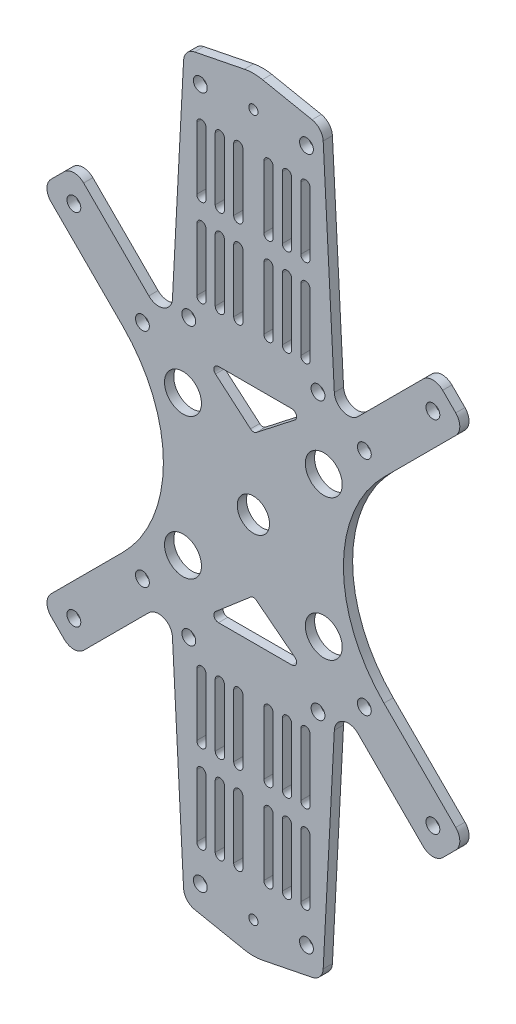
SolidWorks part; units mm, degrees
ref_plane "Alzado" through (0, 0, 0) normal (0, 0, 1) x (1, 0, 0)
ref_plane "Planta" through (0, 0, 0) normal (0, 1, 0) x (1, 0, 0)
ref_plane "Vista lateral" through (0, 0, 0) normal (1, 0, 0) x (0, 0, -1)
sketch "Croquis1" plane through (0, 0, 0) normal (0, 0, 1) x (1, 0, 0)
  line L0 (0, 0) -> (27.8544, 27.8544) construction
  line L1 (0, 0) -> (-42.4264, 42.4264) construction
  line L2 (0, 0) -> (0, 42.4264) construction
  line L3 (15.25, -15.25) -> (-15.25, -15.25) construction
  line L4 (15.25, -15.25) -> (15.25, 15.25) construction
  line L5 (15.25, 15.25) -> (-15.25, 15.25) construction
  line L6 (-15.25, -15.25) -> (-15.25, 15.25) construction
  line L7 (15.25, -15.25) -> (-15.25, 15.25) construction
  line L8 (15.25, 15.25) -> (-15.25, -15.25) construction
  line L9 (0, 42.4264) -> (-20, 42.4264) construction
  line L10 (-42.4264, 42.4264) -> (-38.8909, 45.9619)
  line L11 (-38.8909, 45.9619) -> (-31.0962, 38.1673)
  line L13 (-42.4264, 42.4264) -> (-45.9619, 38.8909)
  line L14 (-45.9619, 38.8909) -> (-38.1673, 31.0962)
  line L16 (38.8909, 45.9619) -> (31.0962, 38.1673)
  line L17 (42.4264, 42.4264) -> (38.8909, 45.9619)
  line L18 (42.4264, 42.4264) -> (45.9619, 38.8909)
  line L19 (-45.9619, -38.8909) -> (-38.1673, -31.0962)
  line L20 (0, 0) -> (-15.25, 0) construction
  line L21 (45.9619, 38.8909) -> (38.1673, 31.0962)
  line L22 (42.4264, -42.4264) -> (45.9619, -38.8909)
  line L23 (42.4264, -42.4264) -> (38.8909, -45.9619)
  line L24 (38.8909, -45.9619) -> (31.0962, -38.1673)
  line L27 (-38.8909, -45.9619) -> (-31.0962, -38.1673)
  line L28 (-42.4264, -42.4264) -> (-38.8909, -45.9619)
  line L29 (-42.4264, -42.4264) -> (-45.9619, -38.8909)
  line L30 (45.9619, -38.8909) -> (38.1673, -31.0962)
  line L31 (-15, 80) -> (15, 80) construction
  line L32 (0, -15.25) -> (0, -80) construction
  line L36 (-15, -80) -> (15, -80) construction
  line L41 (-12.268, -54) -> (-12.268, -67.5)
  line L43 (-10.268, -54) -> (-10.268, -67.5)
  line L105 (0, -80) -> (0, -83) construction
  line L106 (-15, -80) -> (0, -83)
  line L127 (15, -80) -> (0, -83)
  line L131 (0, 80) -> (0, 83) construction
  line L132 (-15, 80) -> (15, 80) construction
  line L136 (15, 80) -> (0, 83)
  line L157 (-15, 80) -> (0, 83)
  line L160 (-14, 30) -> (-17.8891, 33.8891) construction
  line L161 (-31.0962, 38.1673) -> (-22.6531, 29.7242)
  line L162 (-17.5359, 31.6883) -> (-15, 80)
  line L163 (17.5359, 31.6883) -> (15, 80)
  line L164 (31.0962, 38.1673) -> (22.6531, 29.7242)
  line L165 (31.0962, -38.1673) -> (22.6531, -29.7242)
  line L166 (17.5359, -31.6883) -> (15, -80)
  line L167 (-17.5359, -31.6883) -> (-15, -80)
  line L168 (-31.0962, -38.1673) -> (-22.6531, -29.7242)
  line L169 (-8.268, -54) -> (-8.268, -67.5)
  line L170 (-6.268, -54) -> (-6.268, -67.5)
  line L171 (-4.268, -54) -> (-4.268, -67.5)
  line L172 (-2.268, -54) -> (-2.268, -67.5)
  line L173 (-8.268, -35) -> (-8.268, -48.5)
  line L174 (-6.268, -35) -> (-6.268, -48.5)
  line L175 (-4.268, -35) -> (-4.268, -48.5)
  line L176 (-2.268, -35) -> (-2.268, -48.5)
  line L177 (-12.268, -35) -> (-12.268, -48.5)
  line L178 (-10.268, -35) -> (-10.268, -48.5)
  line L179 (10.268, -35) -> (10.268, -48.5)
  line L180 (12.268, -35) -> (12.268, -48.5)
  line L181 (2.268, -35) -> (2.268, -48.5)
  line L182 (4.268, -35) -> (4.268, -48.5)
  line L183 (6.268, -35) -> (6.268, -48.5)
  line L184 (8.268, -35) -> (8.268, -48.5)
  line L185 (2.268, -54) -> (2.268, -67.5)
  line L186 (4.268, -54) -> (4.268, -67.5)
  line L187 (6.268, -54) -> (6.268, -67.5)
  line L188 (8.268, -54) -> (8.268, -67.5)
  line L189 (10.268, -54) -> (10.268, -67.5)
  line L190 (12.268, -54) -> (12.268, -67.5)
  line L191 (12.268, 54) -> (12.268, 67.5)
  line L192 (10.268, 54) -> (10.268, 67.5)
  line L193 (8.268, 54) -> (8.268, 67.5)
  line L194 (6.268, 54) -> (6.268, 67.5)
  line L195 (4.268, 54) -> (4.268, 67.5)
  line L196 (2.268, 54) -> (2.268, 67.5)
  line L197 (8.268, 35) -> (8.268, 48.5)
  line L198 (6.268, 35) -> (6.268, 48.5)
  line L199 (4.268, 35) -> (4.268, 48.5)
  line L200 (2.268, 35) -> (2.268, 48.5)
  line L201 (12.268, 35) -> (12.268, 48.5)
  line L202 (10.268, 35) -> (10.268, 48.5)
  line L203 (-10.268, 35) -> (-10.268, 48.5)
  line L204 (-12.268, 35) -> (-12.268, 48.5)
  line L205 (-2.268, 35) -> (-2.268, 48.5)
  line L206 (-4.268, 35) -> (-4.268, 48.5)
  line L207 (-6.268, 35) -> (-6.268, 48.5)
  line L208 (-8.268, 35) -> (-8.268, 48.5)
  line L209 (-2.268, 54) -> (-2.268, 67.5)
  line L210 (-4.268, 54) -> (-4.268, 67.5)
  line L211 (-6.268, 54) -> (-6.268, 67.5)
  line L212 (-8.268, 54) -> (-8.268, 67.5)
  line L213 (-10.268, 54) -> (-10.268, 67.5)
  line L214 (-12.268, 54) -> (-12.268, 67.5)
  line L215 (-0.621, -15.7817) -> (-8.2129, -22.282)
  line L216 (-7.5625, -24.0416) -> (8.3607, -24.0416)
  line L217 (8.9758, -22.2532) -> (0.6445, -15.7529)
  line L218 (-7.5625, 24.0416) -> (8.3607, 24.0416)
  line L219 (8.9758, 22.2532) -> (0.6445, 15.7529)
  line L220 (-0.621, 15.7817) -> (-8.2129, 22.282)
  line L221 (-38.1673, 31.0962) -> (-28.2843, 21.2132)
  line L222 (-28.2843, -21.2132) -> (-38.1673, -31.0962)
  line L223 (28.2843, -21.2132) -> (38.1673, -31.0962)
  line L224 (38.1673, 31.0962) -> (28.2843, 21.2132)
  circle A0 centre (-15.25, 15.25) radius 4
  circle A1 centre (-24.0416, 24.0416) radius 1.5
  circle A2 centre (-38.8909, 38.8909) radius 1.5
  circle A5 centre (38.8909, 38.8909) radius 1.5
  circle A6 centre (24.0416, 24.0416) radius 1.5
  circle A7 centre (15.25, 15.25) radius 4
  circle A8 centre (15.25, -15.25) radius 4
  circle A9 centre (24.0416, -24.0416) radius 1.5
  circle A10 centre (38.8909, -38.8909) radius 1.5
  circle A12 centre (-15.25, -15.25) radius 4
  circle A13 centre (-24.0416, -24.0416) radius 1.5
  circle A14 centre (-38.8909, -38.8909) radius 1.5
  circle A18 centre (0, 0) radius 3.5
  circle A19 centre (-11.5, -75) radius 1.5
  circle A21 centre (-14, 30) radius 1.5
  arc A27 (-12.268, -54) -> (-10.268, -54) centre (-11.268, -54) cw
  arc A28 (-12.268, -67.5) -> (-10.268, -67.5) centre (-11.268, -67.5) ccw
  circle A111 centre (11.5, -75) radius 1.5
  circle A112 centre (11.5, 75) radius 1.5
  circle A137 centre (-11.5, 75) radius 1.5
  arc A138 (-22.6531, 29.7242) -> (-17.5359, 31.6883) centre (-20.5318, 31.8455) ccw
  arc A139 (22.6531, 29.7242) -> (17.5359, 31.6883) centre (20.5318, 31.8455) cw
  arc A140 (22.6531, -29.7242) -> (17.5359, -31.6883) centre (20.5318, -31.8455) ccw
  arc A141 (-22.6531, -29.7242) -> (-17.5359, -31.6883) centre (-20.5318, -31.8455) cw
  circle A142 centre (14, 30) radius 1.5
  circle A143 centre (14, -30) radius 1.5
  circle A144 centre (-14, -30) radius 1.5
  arc A145 (-8.268, -67.5) -> (-6.268, -67.5) centre (-7.268, -67.5) ccw
  arc A146 (-8.268, -54) -> (-6.268, -54) centre (-7.268, -54) cw
  arc A147 (-4.268, -67.5) -> (-2.268, -67.5) centre (-3.268, -67.5) ccw
  arc A148 (-4.268, -54) -> (-2.268, -54) centre (-3.268, -54) cw
  arc A149 (-8.268, -48.5) -> (-6.268, -48.5) centre (-7.268, -48.5) ccw
  arc A150 (-8.268, -35) -> (-6.268, -35) centre (-7.268, -35) cw
  arc A151 (-4.268, -48.5) -> (-2.268, -48.5) centre (-3.268, -48.5) ccw
  arc A152 (-4.268, -35) -> (-2.268, -35) centre (-3.268, -35) cw
  arc A153 (-12.268, -48.5) -> (-10.268, -48.5) centre (-11.268, -48.5) ccw
  arc A154 (-12.268, -35) -> (-10.268, -35) centre (-11.268, -35) cw
  arc A155 (12.268, -35) -> (10.268, -35) centre (11.268, -35) ccw
  arc A156 (12.268, -48.5) -> (10.268, -48.5) centre (11.268, -48.5) cw
  arc A157 (4.268, -35) -> (2.268, -35) centre (3.268, -35) ccw
  arc A158 (4.268, -48.5) -> (2.268, -48.5) centre (3.268, -48.5) cw
  arc A159 (8.268, -35) -> (6.268, -35) centre (7.268, -35) ccw
  arc A160 (8.268, -48.5) -> (6.268, -48.5) centre (7.268, -48.5) cw
  arc A161 (4.268, -54) -> (2.268, -54) centre (3.268, -54) ccw
  arc A162 (4.268, -67.5) -> (2.268, -67.5) centre (3.268, -67.5) cw
  arc A163 (8.268, -54) -> (6.268, -54) centre (7.268, -54) ccw
  arc A164 (8.268, -67.5) -> (6.268, -67.5) centre (7.268, -67.5) cw
  arc A165 (12.268, -67.5) -> (10.268, -67.5) centre (11.268, -67.5) cw
  arc A166 (12.268, -54) -> (10.268, -54) centre (11.268, -54) ccw
  arc A167 (12.268, 54) -> (10.268, 54) centre (11.268, 54) cw
  arc A168 (12.268, 67.5) -> (10.268, 67.5) centre (11.268, 67.5) ccw
  arc A169 (8.268, 67.5) -> (6.268, 67.5) centre (7.268, 67.5) ccw
  arc A170 (8.268, 54) -> (6.268, 54) centre (7.268, 54) cw
  arc A171 (4.268, 67.5) -> (2.268, 67.5) centre (3.268, 67.5) ccw
  arc A172 (4.268, 54) -> (2.268, 54) centre (3.268, 54) cw
  arc A173 (8.268, 48.5) -> (6.268, 48.5) centre (7.268, 48.5) ccw
  arc A174 (8.268, 35) -> (6.268, 35) centre (7.268, 35) cw
  arc A175 (4.268, 48.5) -> (2.268, 48.5) centre (3.268, 48.5) ccw
  arc A176 (4.268, 35) -> (2.268, 35) centre (3.268, 35) cw
  arc A177 (12.268, 48.5) -> (10.268, 48.5) centre (11.268, 48.5) ccw
  arc A178 (12.268, 35) -> (10.268, 35) centre (11.268, 35) cw
  arc A179 (-12.268, 35) -> (-10.268, 35) centre (-11.268, 35) ccw
  arc A180 (-12.268, 48.5) -> (-10.268, 48.5) centre (-11.268, 48.5) cw
  arc A181 (-4.268, 35) -> (-2.268, 35) centre (-3.268, 35) ccw
  arc A182 (-4.268, 48.5) -> (-2.268, 48.5) centre (-3.268, 48.5) cw
  arc A183 (-8.268, 35) -> (-6.268, 35) centre (-7.268, 35) ccw
  arc A184 (-8.268, 48.5) -> (-6.268, 48.5) centre (-7.268, 48.5) cw
  arc A185 (-4.268, 54) -> (-2.268, 54) centre (-3.268, 54) ccw
  arc A186 (-4.268, 67.5) -> (-2.268, 67.5) centre (-3.268, 67.5) cw
  arc A187 (-8.268, 54) -> (-6.268, 54) centre (-7.268, 54) ccw
  arc A188 (-8.268, 67.5) -> (-6.268, 67.5) centre (-7.268, 67.5) cw
  arc A189 (-12.268, 67.5) -> (-10.268, 67.5) centre (-11.268, 67.5) cw
  arc A190 (-12.268, 54) -> (-10.268, 54) centre (-11.268, 54) ccw
  arc A191 (8.3607, -24.0416) -> (8.9758, -22.2532) centre (8.3607, -23.0416) ccw
  arc A192 (0.6445, -15.7529) -> (-0.621, -15.7817) centre (0.0294, -16.5413) ccw
  arc A193 (-8.2129, -22.282) -> (-7.5625, -24.0416) centre (-7.5625, -23.0416) ccw
  arc A194 (8.3607, 24.0416) -> (8.9758, 22.2532) centre (8.3607, 23.0416) cw
  arc A195 (0.6445, 15.7529) -> (-0.621, 15.7817) centre (0.0294, 16.5413) cw
  arc A196 (-8.2129, 22.282) -> (-7.5625, 24.0416) centre (-7.5625, 23.0416) cw
  arc A197 (-28.2843, 21.2132) -> (-28.2843, -21.2132) centre (-49.4975, 0) cw
  arc A198 (28.2843, 21.2132) -> (28.2843, -21.2132) centre (49.4975, 0) ccw
  circle A199 centre (0, 76) radius 1
  circle A200 centre (0, -76) radius 1
  point P35 (-34.9935, 42.0646)
  point P37 (44.1942, 40.6586)
  point P45 (44.1942, -40.6586)
  point P52 (-16.268, -55.8441)
  point P61 (-34.9935, -42.0646)
  point P70 (0, 80)
  point P260 (-7.0711, 0)
  dimension "D2" = 8
  dimension "D4" = 5
  dimension "D8" = 14.75
  dimension "D10" = 3
  dimension "D11" = 3
  dimension "D13" = 11.5
  dimension "D15" = 3
  dimension "D16" = 14
  dimension "D18" = 3
  dimension "D24" = 3
  dimension "D26" = 1
  dimension "D27" = 7
  dimension "D28" = 30
  dimension "D29" = 7
  dimension "D1" = 30.5
  dimension "D3" = 60
  dimension "D5" = 21
  dimension "D6" = 15
  dimension "D7" = 5
  dimension "D9" = 5
  dimension "D12" = 80
  dimension "D14" = 5
  dimension "D17" = 4
  dimension "D19" = 2
  dimension "D20" = 13.5
  dimension "D21" = 7.5
  dimension "D22" = 3
  dimension "D25" = 2
  dimension "D23" = 5.5
extrude "Saliente-Extruir1" add sketch "Croquis1" along normal blind 2
fillet "Redondeo1" radius 3 12 edges at (45.9619, -38.8909, 1) (38.8909, -45.9619, 1) (-45.9619, -38.8909, 1) (-38.8909, -45.9619, 1) (45.9619, 38.8909, 1) (38.8909, 45.9619, 1) (-38.8909, 45.9619, 1) (-45.9619, 38.8909, 1) (15, 80, 1) (-15, 80, 1) (15, -80, 1) (-15, -80, 1)
fillet "Redondeo2" radius 10 2 edges at (0, -83, 1) (0, 83, 1)
